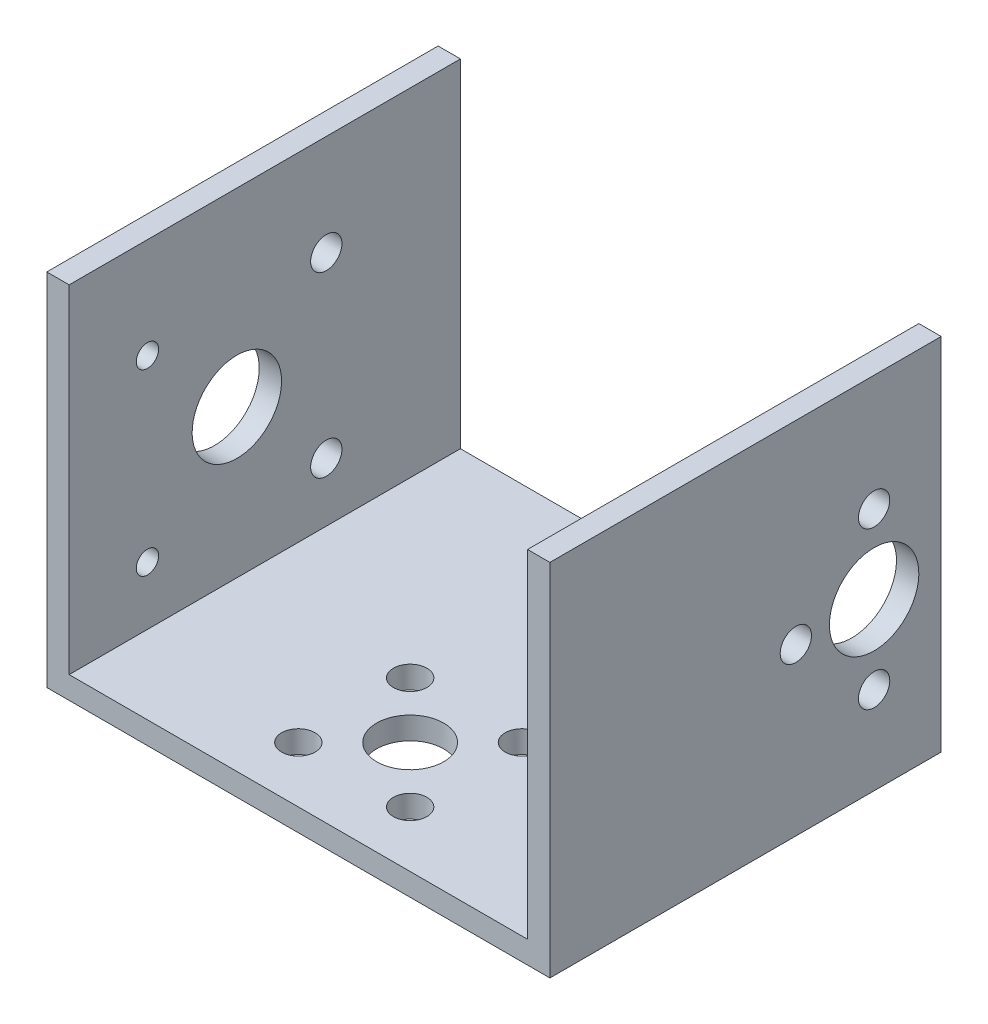
SolidWorks part; units mm, degrees
ref_plane "前视基准面" through (0, 0, 0) normal (0, 0, 1) x (1, 0, 0)
ref_plane "上视基准面" through (0, 0, 0) normal (0, 1, 0) x (1, 0, 0)
ref_plane "右视基准面" through (0, 0, 0) normal (1, 0, 0) x (0, 0, -1)
other "Configuration Table"
sketch "草图1" plane through (0, 0, 0) normal (0, 0, 1) x (1, 0, 0)
  line L0 (114.631, 0) -> (-114.631, 0) construction
  line L1 (0, -79.5371) -> (0, 79.5371) construction
  line L4 (22.5, 1.0976) -> (22.5, -1.0976)
  line L5 (22.5, -1.0976) -> (-22.5, -1.0976)
  line L6 (-22.5, 1.0976) -> (-22.5, -1.0976)
  line L7 (0, -1.0976) -> (0, 1) construction
  line L8 (22.5, 0) -> (-22.5, 0) construction
  line L14 (-22.5, 1.0976) -> (-22.5, 31.0976)
  line L15 (-22.5, 31.0976) -> (-20.5, 31.0976)
  line L16 (-20.5, 0.9024) -> (-20.5, 31.0976)
  line L17 (20.5, 0.9024) -> (20.5, 31.0976)
  line L18 (22.5, 31.0976) -> (20.5, 31.0976)
  line L19 (22.5, 1.0976) -> (22.5, 31.0976)
  line L20 (20.5, 0.9024) -> (-20.5, 0.9024)
  point P0 (0, 0)
  point P4 (0, 0)
  point P7 (0, 0)
  dimension "D1" = 2
  dimension "D3" = 45
  dimension "D4" = 30
extrude "凸台-拉伸1" add sketch "草图1" along normal blind 20
sketch "草图2" plane through (-22.5, 0, 0) normal (-1, 0, 0) x (0, 0, 1)
  line L0 (20, -1.0976) -> (0, -1.0976) construction
  line L2 (10, 14.1463) -> (14, 14.1463) construction
  circle A0 centre (10, 14.1463) radius 4
  dimension "D1" = 15.2439
  dimension "D2" = 4
extrude "切除-拉伸1" cut sketch "草图2" against normal up to next and the other way through all
sketch "草图3" plane through (-22.5, 0, 0) normal (-1, 0, 0) x (0, 0, 1)
  line L0 (0, 22.0963) -> (2, 22.0963) construction
  line L1 (0, 31.0976) -> (0, -1.0976) construction
  line L4 (20, 22.122) -> (18, 22.122) construction
  line L6 (20, 6.122) -> (18, 6.122) construction
  line L7 (0, 6.172) -> (2, 6.172) construction
  line L8 (20, -1.0976) -> (0, -1.0976) construction
  circle A1 centre (2, 22.0963) radius 1.4
  circle A2 centre (18, 22.122) radius 1
  circle A3 centre (18, 6.122) radius 1
  circle A4 centre (2, 6.172) radius 1.4
  dimension "D2" = 7.2695
  dimension "D1" = 23.1939
extrude "切除-拉伸2" cut sketch "草图3" against normal up to next
sketch "草图7" plane through (22.5, 0, 0) normal (1, 0, 0) x (0, 0, -1)
  line L0 (0, 15) -> (0, 29.5749) construction
  line L1 (0, -1.0976) -> (0, 31.0976) construction
  line L2 (0, -1.0976) -> (10, -1.0976) construction
  line L4 (0, 31.0976) -> (10, 31.0976)
  line L5 (0, 31.0976) -> (0, -1.0976)
  line L6 (0, -1.0976) -> (10, -1.0976)
  line L7 (10, 31.0976) -> (10, -1.0976)
extrude "凸台-拉伸2" add sketch "草图7" against normal blind 2
sketch "草图8" plane through (0, -1.0976, 0) normal (0, -1, 0) x (1, 0, 0)
  line L0 (0, 0) -> (-28.7147, 0) construction
  line L1 (21.5, -10) -> (-22.6749, -10) construction
  line L2 (20.5, -10) -> (22.5, -10) construction
  line L8 (-22.5, 0) -> (20.5, 0)
  line L9 (-22.5, 0) -> (-22.5, -10)
  line L10 (-22.5, -10) -> (20.5, -10)
  line L11 (20.5, 0) -> (20.5, -10)
extrude "凸台-拉伸3" add sketch "草图8" against normal blind 2
sketch "草图9" plane through (-22.5, 0, 0) normal (-1, 0, 0) x (0, 0, 1)
  line L0 (0, 31.0976) -> (-10, 31.0976) construction
  line L2 (-10, 31.0976) -> (0, 31.0976)
  line L3 (-10, 31.0976) -> (-10, 0.9024)
  line L4 (-10, 0.9024) -> (0, 0.9024)
  line L5 (0, 31.0976) -> (0, 0.9024)
extrude "凸台-拉伸4" add sketch "草图9" against normal blind 2
sketch "草图11" plane through (22.5, 0, 0) normal (1, 0, 0) x (0, 0, -1)
  line L0 (4, 13.7415) -> (-3, 13.7415) construction
  line L1 (-20, 20.7415) -> (4, 20.7415) construction
  line L2 (4, 20.7415) -> (4, 6.7415) construction
  line L3 (0, -1.1659) -> (0, 14.8341) construction
  line L6 (-20, -1.0976) -> (-20, 31.0976) construction
  line L7 (-3, 13.7415) -> (-3, -1.1659) construction
  circle A5 centre (4, 20.7415) radius 1.4
  circle A6 centre (4, 6.7415) radius 1.4
  circle A7 centre (-3, 13.7415) radius 1.4
  circle A8 centre (4, 13.7415) radius 4
extrude "切除-拉伸8" cut sketch "草图11" against normal blind 2
sketch "草图13" plane through (0, -1.0976, 0) normal (0, -1, 0) x (1, 0, 0)
  line L0 (-22.5, 20) -> (-22.5, 25) construction
  line L1 (22.5, 20) -> (22.5, 25) construction
  line L2 (-22.5, 25) -> (22.5, 25)
  line L3 (-22.5, 20) -> (22.5, 20)
  line L4 (22.5, 25) -> (22.5, 20)
  line L5 (-22.5, 25) -> (-22.5, 20)
extrude "凸台-拉伸5" add sketch "草图13" against normal blind 2
sketch "草图14" plane through (0, 0.9024, 0) normal (0, 1, 0) x (1, 0, 0)
  line L1 (20.5, -20) -> (22.5, -20)
  line L2 (20.5, -20) -> (20.5, -25)
  line L3 (20.5, -25) -> (22.5, -25)
  line L4 (22.5, -20) -> (22.5, -25)
  line L5 (-20.5, -20) -> (-22.5, -20)
  line L6 (-20.5, -20) -> (-20.5, -25)
  line L7 (-20.5, -25) -> (-22.5, -25)
  line L8 (-22.5, -20) -> (-22.5, -25)
extrude "凸台-拉伸6" add sketch "草图14" along normal blind 30.1951
sketch "草图19" plane through (0, -1.0976, 0) normal (0, -1, 0) x (1, 0, 0)
  line L0 (-22.5, 20) -> (-5, 20) construction
  line L1 (-22.5, 25) -> (-22.5, -10) construction
  line L2 (22.5, 25) -> (-22.5, 25) construction
  line L3 (-22.5, 15) -> (0, 15) construction
  line L4 (0, 15) -> (0, 19.8807) construction
  circle A0 centre (-5, 20) radius 1.5
  circle A1 centre (0, 15) radius 3
  circle A2 centre (-5, 10) radius 1.5
  circle A3 centre (5, 10) radius 1.5
  circle A4 centre (5, 20) radius 1.5
  dimension "D2" = 10
  dimension "D1" = 5
extrude "切除-拉伸9" cut sketch "草图19" against normal up to next
